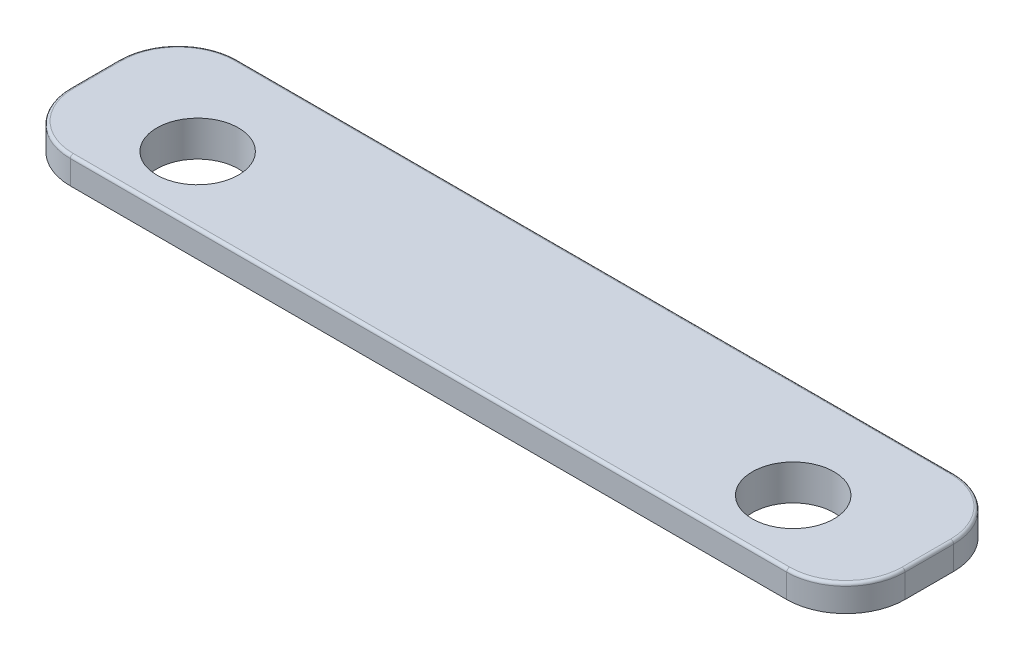
SolidWorks part; units mm, degrees
ref_plane "Front Plane" through (0, 0, 0) normal (0, 0, 1) x (1, 0, 0)
ref_plane "Top Plane" through (0, 0, 0) normal (0, 1, 0) x (1, 0, 0)
ref_plane "Right Plane" through (0, 0, 0) normal (1, 0, 0) x (0, 0, -1)
sketch "Sketch1" plane through (0, 0, 0) normal (0, 1, 0) x (1, 0, 0)
  line L1 (-17.907, 3.5814) -> (17.907, 3.5814)
  line L2 (-17.907, 3.5814) -> (-17.907, -3.5814)
  line L3 (-17.907, -3.5814) -> (17.907, -3.5814)
  line L4 (17.907, 3.5814) -> (17.907, -3.5814)
  dimension "D1" = 35.814
  dimension "D2" = 17.907
  dimension "D3" = 7.1628
  dimension "D4" = 3.5814
extrude "Boss-Extrude1" add sketch "Sketch1" along normal blind 1.524
fillet "Fillet1" radius 2.54 4 edges at (-17.907, 0.762, -3.5814) (-17.907, 0.762, 3.5814) (17.907, 0.762, -3.5814) (17.907, 0.762, 3.5814)
fillet "Fillet2" radius 0.127 8 edges at (17.1631, 1.524, 2.8375) (0, 1.524, 3.5814) (-17.1631, 1.524, 2.8375) (-17.907, 1.524, 0) (-17.1631, 1.524, -2.8375) (0, 1.524, -3.5814) (17.1631, 1.524, -2.8375) (17.907, 1.524, 0)
sketch "Sketch4" plane through (0, 0.381, 0) normal (0, -1, 0) x (1, 0, 0)
  line L1 (-15.367, 2.9464) -> (-15.367, 3.2004)
  line L2 (-17.526, 1.0414) -> (-17.526, -1.0414)
  line L3 (-17.526, 1.0414) -> (-17.526, -1.0414)
  line L4 (-15.367, -2.9464) -> (-15.367, -3.2004)
  line L6 (-17.272, 1.0414) -> (-17.272, -1.0414) construction
  line L7 (-17.272, 1.0414) -> (-17.272, -1.0414)
  arc A6 (-15.367, 3.2004) -> (-17.526, 1.0414) centre (-15.367, 1.0414) ccw
  arc A7 (-15.367, 3.2004) -> (-17.526, 1.0414) centre (-15.367, 1.0414) ccw
  arc A8 (-17.272, -1.0414) -> (-15.367, -2.9464) centre (-15.367, -1.0414) ccw construction
  arc A9 (-17.526, -1.0414) -> (-15.367, -3.2004) centre (-15.367, -1.0414) ccw
  arc A10 (-17.526, -1.0414) -> (-15.367, -3.2004) centre (-15.367, -1.0414) ccw
  arc A11 (-15.367, 2.9464) -> (-17.272, 1.0414) centre (-15.367, 1.0414) ccw construction
  arc A12 (-17.272, -1.0414) -> (-15.367, -2.9464) centre (-15.367, -1.0414) ccw
  arc A13 (-15.367, 2.9464) -> (-17.272, 1.0414) centre (-15.367, 1.0414) ccw
  dimension "D1" = 0.381
  dimension "D2" = 0.381
  dimension "D3" = 0.381
extrude "Boss-Extrude2" add sketch "Sketch4" along normal up to surface (0.381 mm away) up to face at (0, 0, 0)
ref_plane "Plane1" through (0, 0, 0) normal (1, 0, 0) x (0, 0, -1)
mirror "Mirror3" about plane through (0, 0, 0) normal (1, 0, 0) of "Boss-Extrude2"
sketch "Sketch5" plane through (0, 1.524, 0) normal (0, 1, 0) x (1, 0, 0)
  line L0 (-17.907, -1.0414) -> (-17.907, 1.0414) construction
  line L1 (15.367, -3.5814) -> (-15.367, -3.5814) construction
  circle A0 centre (-12.7762, -0.7112) radius 1.2827
  dimension "D1" = 2.5654
  dimension "D2" = 5.1308
  dimension "D3" = 2.8702
extrude "Cut-Extrude2" cut sketch "Sketch5" against normal blind 2.54
sketch "Sketch9" plane through (0, 1.524, 0) normal (0, 1, 0) x (1, 0, 0)
  circle A1 centre (-12.7762, -0.7112) radius 1.7526
  dimension "D1" = 3.5052
extrude "Cut-Extrude5" cut sketch "Sketch9" against normal blind 1.016
mirror "Mirror4" about plane through (0, 0, 0) normal (1, 0, 0) of "Cut-Extrude2", "Cut-Extrude5"
sketch "Sketch10" plane through (0, 0, 0) normal (0, -1, 0) x (1, 0, 0)
  line L0 (17.907, 1.0414) -> (17.907, -1.0414) construction
  line L1 (15.367, -3.5814) -> (-15.367, -3.5814) construction
  line L2 (-17.907, -1.0414) -> (-17.907, 1.0414) construction
  line L3 (-15.367, 3.5814) -> (15.367, 3.5814) construction
  line L4 (17.907, 1.0414) -> (17.907, -1.0414)
  line L5 (15.367, -3.5814) -> (-15.367, -3.5814)
  line L6 (-17.907, -1.0414) -> (-17.907, 1.0414)
  line L7 (-15.367, 3.5814) -> (15.367, 3.5814)
  line L8 (-15.367, 2.9464) -> (15.367, 2.9464)
  line L9 (17.272, 1.0414) -> (17.272, -1.0414)
  line L10 (15.367, -2.9464) -> (-15.367, -2.9464)
  line L11 (-17.272, -1.0414) -> (-17.272, 1.0414)
  arc A0 (17.907, 1.0414) -> (15.367, 3.5814) centre (15.367, 1.0414) ccw construction
  arc A1 (15.367, -3.5814) -> (17.907, -1.0414) centre (15.367, -1.0414) ccw construction
  arc A2 (-17.907, -1.0414) -> (-15.367, -3.5814) centre (-15.367, -1.0414) ccw construction
  arc A3 (-15.367, 3.5814) -> (-17.907, 1.0414) centre (-15.367, 1.0414) ccw construction
  arc A4 (17.907, 1.0414) -> (15.367, 3.5814) centre (15.367, 1.0414) ccw
  arc A5 (15.367, -3.5814) -> (17.907, -1.0414) centre (15.367, -1.0414) ccw
  arc A6 (-17.907, -1.0414) -> (-15.367, -3.5814) centre (-15.367, -1.0414) ccw
  arc A7 (-15.367, 3.5814) -> (-17.907, 1.0414) centre (-15.367, 1.0414) ccw
  arc A8 (17.272, 1.0414) -> (15.367, 2.9464) centre (15.367, 1.0414) ccw
  arc A9 (15.367, -2.9464) -> (17.272, -1.0414) centre (15.367, -1.0414) ccw
  arc A10 (-17.272, -1.0414) -> (-15.367, -2.9464) centre (-15.367, -1.0414) ccw
  arc A11 (-15.367, 2.9464) -> (-17.272, 1.0414) centre (-15.367, 1.0414) ccw
  dimension "D1" = 0.635
extrude "Cut-Extrude6" cut sketch "Sketch10" against normal blind 0.381
sketch "Sketch17" plane through (0, 0.508, 0) normal (0, 1, 0) x (1, 0, 0)
  circle A0 centre (-12.7762, -0.7112) radius 1.7526 construction
  circle A1 centre (-12.7762, -0.7112) radius 1.7526
extrude "Cut-Extrude11" cut sketch "Sketch17" against normal through all
sketch "Sketch18" plane through (0, 1.524, 0) normal (0, 1, 0) x (1, 0, 0)
  circle A0 centre (12.7762, -0.7112) radius 1.7526 construction
  circle A1 centre (12.7762, -0.7112) radius 1.7526
extrude "Cut-Extrude12" cut sketch "Sketch18" against normal through all
sketch "Sketch19" plane through (0, 0, 0) normal (0, -1, 0) x (1, 0, 0)
  line L0 (15.367, 3.5814) -> (-15.367, 3.5814) construction
  circle A0 centre (0, 0.7112) radius 0.381
  circle A1 centre (-12.7762, 0.7112) radius 1.7526 construction
  dimension "D1" = 2.8702
  dimension "D2" = 12.7762
  dimension "D3" = 0.762
extrude "Cut-Extrude13" cut sketch "Sketch19" against normal blind 0.127
sketch "Sketch20" plane through (0, 0, 0) normal (0, -1, 0) x (1, 0, 0)
  circle A0 centre (0, 0.7112) radius 0.1905
  dimension "D1" = 0.381
extrude "Cut-Extrude14" cut sketch "Sketch20" against normal blind 0.762
